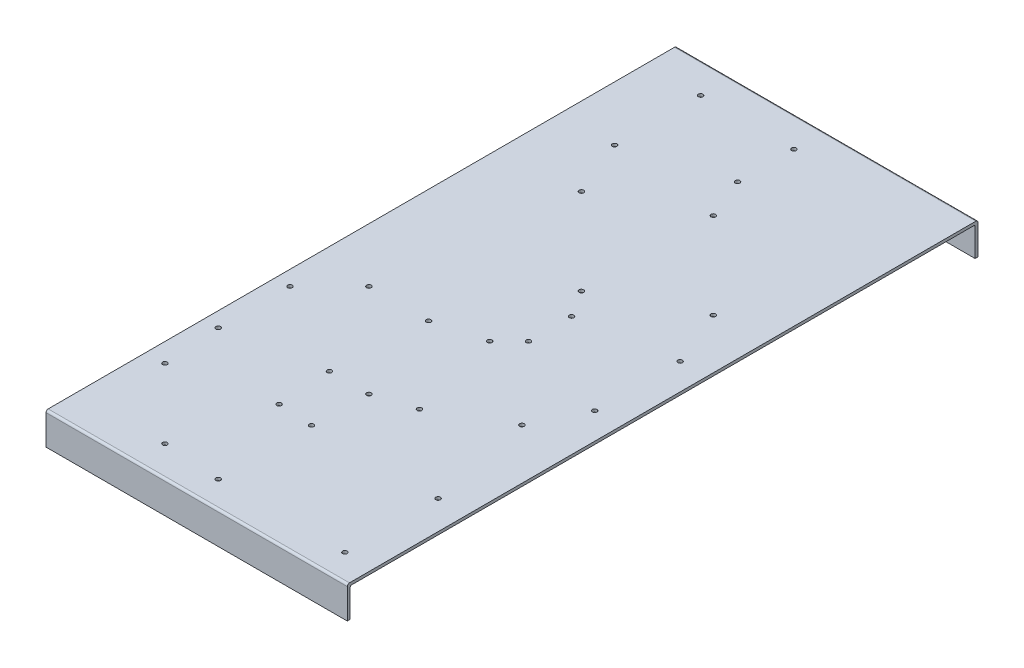
SolidWorks part; units mm, degrees
ref_plane "Front Plane" through (0, 0, 0) normal (0, 0, 1) x (1, 0, 0)
ref_plane "Top Plane" through (0, 0, 0) normal (0, 1, 0) x (1, 0, 0)
ref_plane "Right Plane" through (0, 0, 0) normal (1, 0, 0) x (0, 0, -1)
sketch "Sketch1" plane through (0, 0, 0) normal (0, 1, 0) x (1, 0, 0)
  line L1 (1093.7208, -144.0703) -> (883.7208, -144.0703)
  line L2 (1093.7208, -144.0703) -> (1093.7208, 295.5397)
  line L3 (1093.7208, 295.5397) -> (883.7208, 295.5397)
  line L4 (883.7208, -144.0703) -> (883.7208, 295.5397)
  dimension "D1" = 210
  dimension "D2" = 439.61
extrude "Boss-Extrude1" add sketch "Sketch1" along normal blind 2
sketch "Sketch2" plane through (0, 0, 0) normal (0, -1, 0) x (1, 0, 0)
  line L0 (883.7208, -295.5397) -> (883.7208, 144.0703) construction
  line L1 (1093.7208, 144.0703) -> (883.7208, 144.0703)
  line L2 (1093.7208, 144.0703) -> (1093.7208, 142.0703)
  line L3 (1093.7208, 142.0703) -> (883.7208, 142.0703)
  line L4 (883.7208, 144.0703) -> (883.7208, 142.0703)
  line L6 (1093.7208, -295.5397) -> (883.7208, -295.5397)
  line L7 (1093.7208, -295.5397) -> (1093.7208, -293.5397)
  line L8 (1093.7208, -293.5397) -> (883.7208, -293.5397)
  line L9 (883.7208, -295.5397) -> (883.7208, -293.5397)
  dimension "D1" = 2
  dimension "D2" = 2
extrude "Boss-Extrude2" add sketch "Sketch2" along normal blind 20.32
fillet "Fillet1" radius 1 2 edges at (988.7208, 0, -293.5397) (988.7208, 0, 142.0703)
fillet "Fillet2" radius 1.5 2 edges at (988.7208, 2, 144.0703) (988.7208, 2, -295.5397)
sketch "Sketch3" plane through (0, 2, 0) normal (0, 1, 0) x (1, 0, 0)
  line L0 (929.4208, 294.0397) -> (929.4208, 194.0397)
  line L1 (996.5656, -14.3486) -> (1067.8092, 26.7839)
  line L2 (1093.7208, 294.0397) -> (883.7208, 294.0397) construction
  line L3 (929.4208, 194.0397) -> (1017.8092, 105.6514)
  line L4 (1017.8092, 105.6514) -> (1017.8092, 55.6514)
  line L5 (1017.8092, 55.6514) -> (983.1681, 35.6514)
  line L6 (983.1681, 35.6514) -> (901.5656, 35.6514)
  line L7 (901.5656, 35.6514) -> (901.5656, -54.3486)
  line L8 (965.4537, -118.2368) -> (1093.7208, -118.2368)
  line L9 (1093.7208, -142.5703) -> (1093.7208, 294.0397) construction
  line L10 (1093.7208, -68.2368) -> (965.4537, -68.2368)
  line L11 (951.5656, -54.3486) -> (951.5656, -14.3486)
  line L12 (1067.8092, 26.7839) -> (1067.8092, 126.3621)
  line L13 (951.5656, -14.3486) -> (996.5656, -14.3486)
  line L14 (1067.8092, 126.3621) -> (979.4208, 214.7504)
  line L15 (979.4208, 214.7504) -> (979.4208, 294.0397)
  arc A0 (901.5656, -54.3486) -> (965.4537, -118.2368) centre (965.4537, -54.3486) ccw
  arc A1 (965.4537, -68.2368) -> (951.5656, -54.3486) centre (965.4537, -54.3486) cw
  dimension "D2" = 50
  dimension "D1" = 50
  dimension "D3" = 135
  dimension "D4" = 120
  dimension "D5" = 50
  dimension "D6" = 50
  dimension "D7" = 50
  dimension "D8" = 50
  dimension "D9" = 50
  dimension "D10" = 100
  dimension "D11" = 125
  dimension "D12" = 50
  dimension "D13" = 40
  dimension "D14" = 40
  dimension "D15" = 114.3
  dimension "D16" = 128.2671
  dimension "D17" = 45
sketch "Sketch4" plane through (0, 2, 0) normal (0, 1, 0) x (1, 0, 0)
  line L0 (929.4208, 294.0397) -> (929.4208, 194.0397) construction
  line L2 (1017.8092, 105.6514) -> (1017.8092, 55.6514) construction
  line L4 (983.1681, 35.6514) -> (901.5656, 35.6514) construction
  line L5 (901.5656, 35.6514) -> (901.5656, -54.3486) construction
  line L6 (965.4537, -118.2368) -> (1093.7208, -118.2368) construction
  line L7 (1093.7208, -68.2368) -> (965.4537, -68.2368) construction
  line L8 (951.5656, -14.3486) -> (996.5656, -14.3486) construction
  line L11 (979.4208, 214.7504) -> (979.4208, 294.0397) construction
  circle A0 centre (921.9208, 214.0397) radius 1.6
  circle A1 centre (921.9208, 274.0397) radius 1.6
  circle A2 centre (986.9208, 234.7504) radius 1.6
  circle A3 centre (986.9208, 274.0397) radius 1.6
  circle A8 centre (1010.3092, 65.6514) radius 1.6
  circle A9 centre (1010.3092, 95.6514) radius 1.6
  circle A16 centre (986.5656, -21.8486) radius 1.6
  circle A17 centre (959.0656, -21.8486) radius 1.6
  circle A18 centre (963.1681, 43.1514) radius 1.6
  circle A19 centre (921.5656, 43.1514) radius 1.6
  circle A20 centre (894.0656, -34.3486) radius 1.6
  circle A21 centre (894.0656, 15.6514) radius 1.6
  circle A22 centre (961.3707, -59.264) radius 1.6
  circle A23 centre (945.4537, -122.8799) radius 1.6
  circle A24 centre (896.9225, -74.3486) radius 1.6
  circle A25 centre (1073.7208, -60.7368) radius 1.6
  circle A26 centre (985.4537, -60.7368) radius 1.6
  circle A27 centre (1073.7208, -125.7368) radius 1.6
  circle A28 centre (985.4537, -125.7368) radius 1.6
  arc A29 (901.5656, -54.3486) -> (965.4537, -118.2368) centre (965.4537, -54.3486) ccw construction
  arc A30 (951.5656, -54.3486) -> (965.4537, -68.2368) centre (965.4537, -54.3486) ccw construction
  circle A31 centre (1013.306, -13.3437) radius 1.6
  circle A32 centre (1058.5642, 12.7868) radius 1.6
  circle A33 centre (996.7465, 52.1511) radius 1.6
  circle A34 centre (938.3529, 174.501) radius 1.6
  circle A35 centre (998.457, 114.3969) radius 1.6
  circle A36 centre (998.8663, 205.9116) radius 1.6
  circle A37 centre (1058.9703, 145.8075) radius 1.6
  circle A38 centre (1075.3082, 106.3617) radius 1.6
  circle A39 centre (1075.3054, 46.7817) radius 1.6
  dimension "D1" = 3.2
  dimension "D2" = 3.2
  dimension "D3" = 3.2
  dimension "D4" = 3.2
  dimension "D5" = 3.2
  dimension "D6" = 3.2
  dimension "D7" = 3.2
  dimension "D8" = 3.2
  dimension "D9" = 3.2
  dimension "D10" = 3.2
  dimension "D11" = 3.2
  dimension "D12" = 3.2
  dimension "D13" = 3.2
  dimension "D18" = 10
  dimension "D20" = 3.2
  dimension "D21" = 3.2
  dimension "D24" = 3.2
  dimension "D25" = 3.2
  dimension "D26" = 3.2
  dimension "D27" = 3.2
  dimension "D30" = 7.5
  dimension "D31" = 7.5
  dimension "D32" = 20
  dimension "D33" = 20
  dimension "D36" = 7.5
  dimension "D37" = 7.5
  dimension "D39" = 10
  dimension "D40" = 7.5
  dimension "D41" = 7.5
  dimension "D42" = 7.5
  dimension "D43" = 7.5
  dimension "D44" = 7.5
  dimension "D45" = 7.5
  dimension "D46" = 7.5
  dimension "D47" = 7.5
  dimension "D48" = 7.5
  dimension "D49" = 7.5
  dimension "D54" = 7.5
  dimension "D55" = 7.5
  dimension "D58" = 20
  dimension "D59" = 20
  dimension "D60" = 20
  dimension "D61" = 20
  dimension "D72" = 7.5
  dimension "D74" = 20
  dimension "D75" = 20
  dimension "D76" = 20
  dimension "D77" = 20
  dimension "D78" = 20
  dimension "D79" = 20
  dimension "D80" = 71.39
  dimension "D81" = 71.39
  dimension "D82" = 20
  dimension "D83" = 20
  dimension "D84" = 6.39
extrude "Cut-Extrude1" cut sketch "Sketch4" against normal through all
